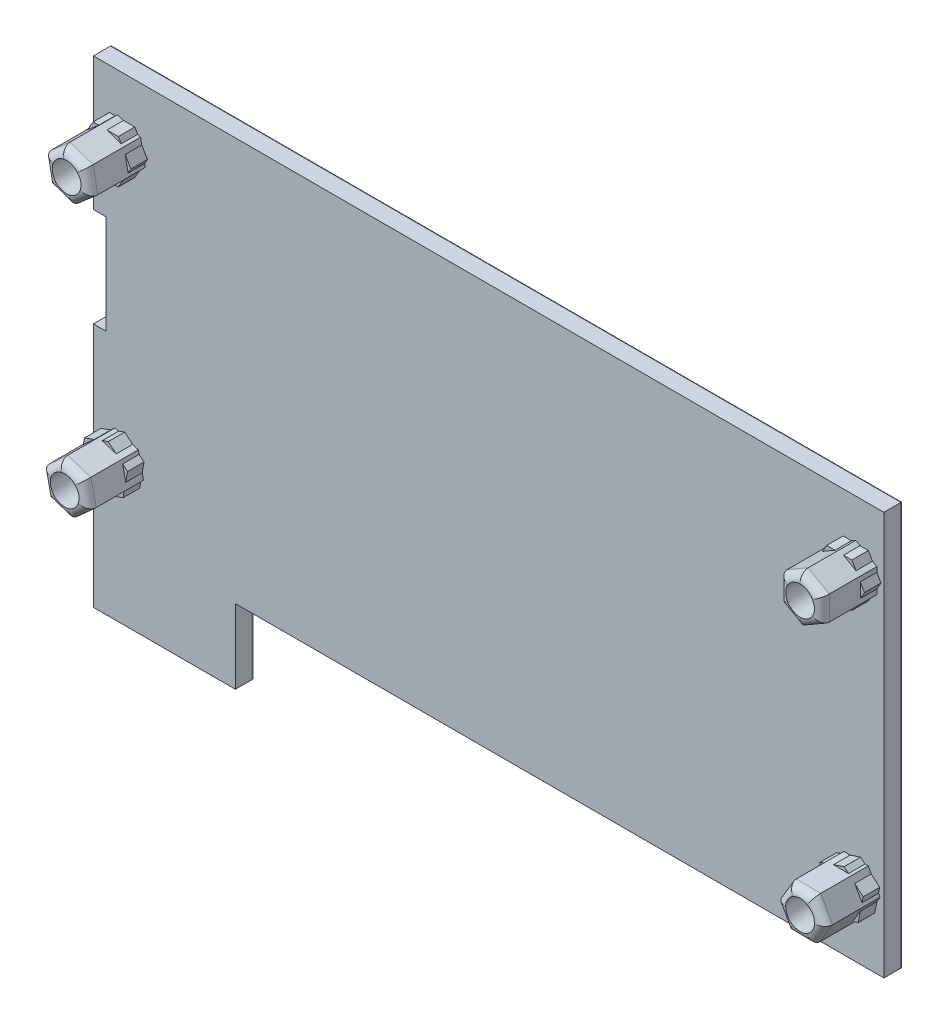
SolidWorks part; units mm, degrees
ref_plane "Front" through (0, 0, 0) normal (0, 0, 1) x (1, 0, 0)
ref_plane "Top" through (0, 0, 0) normal (0, 1, 0) x (1, 0, 0)
ref_plane "Right" through (0, 0, 0) normal (1, 0, 0) x (0, 0, -1)
sketch "Sketch1" plane through (0, 0, 44.2448) normal (0, 0, -1) x (-1, 0, 0)
  line L0 (1.8781, 63) -> (1.8781, 54) construction
  line L6 (19.8781, 54) -> (19.8781, 112.6781) construction
  line L7 (1.8781, 54) -> (19.8781, 54) construction
  line L8 (-76.726, 112.6781) -> (-76.726, 63) construction
  line L9 (19.4781, 63.3614) -> (19.4781, 54.4)
  line L14 (-76.326, 112.2781) -> (19.4781, 112.2781)
  line L15 (-76.326, 112.2781) -> (-76.326, 63.4)
  line L16 (-76.726, 63) -> (1.8781, 63) construction
  line L18 (-76.326, 63.4) -> (2.2781, 63.4)
  line L19 (19.4781, 112.2781) -> (19.4781, 63.3614)
  line L20 (19.4781, 54.4) -> (2.2781, 54.4)
  line L21 (2.2781, 54.4) -> (2.2781, 63.4)
  line L23 (-76.726, 112.6781) -> (19.8781, 112.6781) construction
  dimension "D1" = 0.4
  dimension "D2" = 0.4
  dimension "D3" = 0.4
  dimension "D4" = 0.4
  dimension "D5" = 0.4
  dimension "D6" = 0.4
extrude "back cover" add sketch "Sketch1" against normal up to surface (2.25 mm away)
sketch "Sketch5" plane through (0, 0, 44.2448) normal (0, 0, -1) x (-1, 0, 0)
  line L1 (19.4781, 96.1535) -> (17.9781, 96.1535)
  line L2 (19.4781, 96.1535) -> (19.4781, 84.1535)
  line L3 (19.4781, 84.1535) -> (17.9781, 84.1535)
  line L4 (17.9781, 96.1535) -> (17.9781, 84.1535)
  line L5 (19.4781, 54.4) -> (19.4781, 112.2781) construction
  dimension "D1" = 1.5
  dimension "D2" = 12
extrude "opener access" cut sketch "Sketch5" against normal blind 10
fillet "Fillet1" radius 0.2 10 edges at (37.0239, 63.4, 44.2448) (76.326, 87.839, 44.2448) (28.4239, 112.2781, 44.2448) (-10.8781, 54.4, 44.2448) (-2.2781, 58.9, 44.2448) (-19.4781, 104.2158, 44.2448) (-18.7281, 96.1535, 44.2448) (-17.9781, 90.1535, 44.2448) (-18.7281, 84.1535, 44.2448) (-19.4781, 69.2768, 44.2448)
sketch "Sketch2" plane through (0, 0, 44.2448) normal (0, 0, -1) x (-1, 0, 0)
  line L1 (-72.911, 107.6283) -> (-75.466, 106.1532)
  line L2 (-75.466, 106.1532) -> (-75.466, 103.2029)
  line L3 (-75.466, 103.2029) -> (-72.911, 101.7278)
  line L4 (-72.911, 101.7278) -> (-70.356, 103.2029)
  line L5 (-70.356, 103.2029) -> (-70.356, 106.1532)
  line L6 (-70.356, 106.1532) -> (-72.911, 107.6283)
  line L7 (-74.423, 74.2114) -> (-75.8609, 71.6353)
  line L8 (-75.8609, 71.6353) -> (-74.3489, 69.102)
  line L9 (-74.3489, 69.102) -> (-71.399, 69.1447)
  line L10 (-71.399, 69.1447) -> (-69.961, 71.7208)
  line L11 (-69.961, 71.7208) -> (-71.473, 74.2542)
  line L12 (-71.473, 74.2542) -> (-74.423, 74.2114)
  line L13 (16.8404, 74.5619) -> (14.0318, 73.659)
  line L14 (14.0318, 73.659) -> (13.4094, 70.7751)
  line L15 (13.4094, 70.7751) -> (15.5957, 68.7942)
  line L16 (15.5957, 68.7942) -> (18.4044, 69.6972)
  line L17 (18.4044, 69.6972) -> (19.0268, 72.581)
  line L18 (19.0268, 72.581) -> (16.8404, 74.5619)
  line L19 (16.5474, 107.575) -> (13.7594, 106.6101)
  line L20 (13.7594, 106.6101) -> (13.201, 103.7131)
  line L21 (13.201, 103.7131) -> (15.4307, 101.7811)
  line L22 (15.4307, 101.7811) -> (18.2187, 102.7461)
  line L23 (18.2187, 102.7461) -> (18.777, 105.643)
  line L24 (18.777, 105.643) -> (16.5474, 107.575)
  circle A6 centre (-72.911, 104.6781) radius 2.555 construction
  circle A7 centre (-72.911, 71.6781) radius 2.555 construction
  circle A8 centre (16.2181, 71.6781) radius 2.555 construction
  circle A9 centre (15.989, 104.6781) radius 2.555 construction
extrude "snap in" add sketch "Sketch2" against normal blind 9
sketch "Sketch6" plane through (0, 0, 46.4948) normal (0, 0, -1) x (-1, 0, 0)
  line L0 (-75.466, 106.1532) -> (-70.356, 103.2029) construction
  line L1 (-75.9709, 104.6781) -> (-74.4409, 102.0281)
  line L2 (-74.4409, 102.0281) -> (-71.381, 102.0281)
  line L3 (-71.381, 102.0281) -> (-69.851, 104.6781)
  line L4 (-69.851, 104.6781) -> (-71.381, 107.3281)
  line L5 (-71.381, 107.3281) -> (-74.4409, 107.3281)
  line L6 (-74.4409, 107.3281) -> (-75.9709, 104.6781)
  line L7 (13.7594, 106.6101) -> (18.2187, 102.7461) construction
  line L8 (14.0318, 73.659) -> (18.4044, 69.6972) construction
  line L9 (-74.423, 74.2114) -> (-71.399, 69.1447) construction
  line L11 (-75.8094, 72.6591) -> (-75.2098, 69.6585)
  line L12 (-75.2098, 69.6585) -> (-72.3113, 68.6774)
  line L13 (-72.3113, 68.6774) -> (-70.0125, 70.697)
  line L14 (-70.0125, 70.697) -> (-70.6121, 73.6977)
  line L15 (-70.6121, 73.6977) -> (-73.5106, 74.6787)
  line L16 (-73.5106, 74.6787) -> (-75.8094, 72.6591)
  line L17 (15.6867, 74.6915) -> (13.3427, 72.7246)
  line L18 (13.3427, 72.7246) -> (13.874, 69.7112)
  line L19 (13.874, 69.7112) -> (16.7494, 68.6646)
  line L20 (16.7494, 68.6646) -> (19.0935, 70.6315)
  line L21 (19.0935, 70.6315) -> (18.5622, 73.645)
  line L22 (18.5622, 73.645) -> (15.6867, 74.6915)
  line L23 (12.9291, 104.6781) -> (14.4591, 102.0281)
  line L24 (14.4591, 102.0281) -> (17.519, 102.0281)
  line L25 (17.519, 102.0281) -> (19.049, 104.6781)
  line L26 (19.049, 104.6781) -> (17.519, 107.3281)
  line L27 (17.519, 107.3281) -> (14.4591, 107.3281)
  line L28 (14.4591, 107.3281) -> (12.9291, 104.6781)
  circle A0 centre (-72.911, 104.6781) radius 2.65 construction
  circle A1 centre (-72.911, 71.6781) radius 2.65 construction
  circle A2 centre (16.2181, 71.6781) radius 2.65 construction
  circle A3 centre (15.989, 104.6781) radius 2.65 construction
  point P1 (-72.911, 104.6781)
  dimension "D1" = 5.3
extrude "snap in 2" add sketch "Sketch6" against normal blind 2
fillet "snap in edge rounding" radius 1 24 edges at (-15.4361, 74.1105, 53.2448) (-13.7206, 72.217, 53.2448) (-14.5026, 69.7847, 53.2448) (-17.0001, 69.2457, 53.2448) (-18.7156, 71.1391, 53.2448) (-17.9336, 73.5715, 53.2448) (-15.1534, 107.0926, 53.2448) (-13.4802, 105.1616, 53.2448) (-14.3159, 102.7471, 53.2448) (-16.8247, 102.2636, 53.2448) (-18.4979, 104.1945, 53.2448) (-17.6622, 106.609, 53.2448) (75.1419, 72.9234, 53.2448) (75.1049, 70.3686, 53.2448) (72.8739, 69.1233, 53.2448) (70.68, 70.4328, 53.2448) (70.717, 72.9875, 53.2448) (72.948, 74.2328, 53.2448) (74.1885, 106.8908, 53.2448) (75.466, 104.6781, 53.2448) (74.1885, 102.4654, 53.2448) (71.6335, 102.4654, 53.2448) (70.356, 104.6781, 53.2448) (71.6335, 106.8908, 53.2448)
sketch "Sketch4" plane through (0, 0, 53.2448) normal (0, 0, 1) x (1, 0, 0)
  line L0 (-13.7594, 106.6101) -> (-18.2187, 102.7461) construction
  line L1 (-14.0318, 73.659) -> (-18.4044, 69.6972) construction
  line L2 (74.423, 74.2114) -> (71.399, 69.1447) construction
  line L3 (75.466, 106.1532) -> (70.356, 103.2029) construction
  circle A0 centre (-15.989, 104.6781) radius 1.7409
  circle A1 centre (72.911, 104.6781) radius 1.74
  circle A2 centre (-16.2181, 71.6781) radius 1.74
  circle A3 centre (72.911, 71.6781) radius 1.74
  point P8 (-15.989, 104.6781)
  point P11 (-16.2181, 71.6781)
  point P12 (-15.989, 104.6781)
  point P13 (-13.7594, 106.6101)
  point P18 (72.911, 71.6781)
  point P21 (72.911, 104.6781)
extrude "hollow snap in" cut sketch "Sketch4" against normal blind 3
